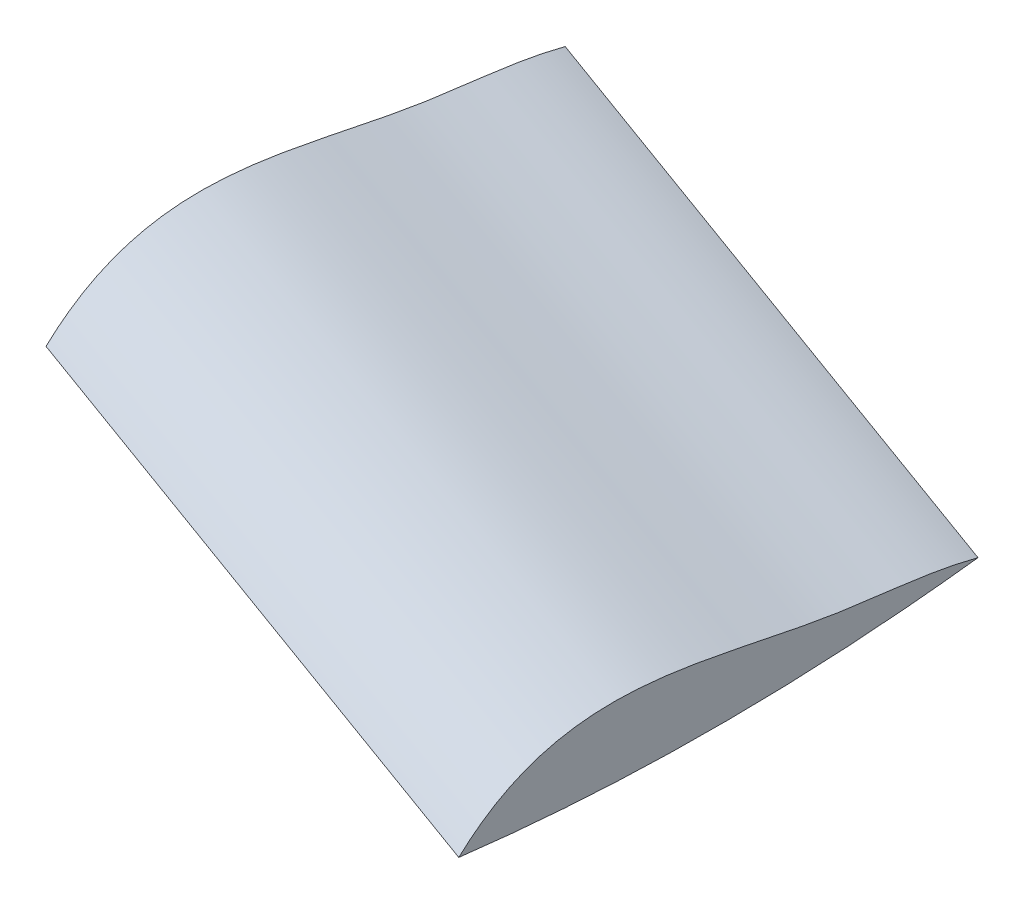
SolidWorks part; units mm, degrees
ref_plane "Front Plane" through (0, 0, 0) normal (0, 0, 1) x (1, 0, 0)
ref_plane "Top Plane" through (0, 0, 0) normal (0, 1, 0) x (1, 0, 0)
ref_plane "Right Plane" through (0, 0, 0) normal (1, 0, 0) x (0, 0, -1)
sketch "Sketch1" plane through (0, 0, 0) normal (1, 0, 0) x (0, 0, -1)
  line L0 (-60.6513, 149.3349) -> (-172.5951, 147.0248) construction
  spline S0 degree 3 poles (-43.701, -3.6751) (60.094, 93.5577) (246.6646, 18.2597) (417.6994, 8.7408) (464.299, -3.6751) knots 0 0 0 0 0.726777 1 1 1 1
  spline S1 degree 2 poles (-43.701, -3.6751) (209.423, -34.3264) (464.299, -3.6751) knots 0 0 0 1 1 1
  point P0 (-43.701, -3.6751)
  point P1 (464.299, -3.6751)
  dimension "D1" = 508
sketch "Sketch2" plane through (0, 0, 0) normal (0, 1, 0) x (1, 0, 0)
  line L0 (0, -185.5968) -> (-635, 45.5243)
  line L1 (0, -43.701) -> (0, 464.299) construction
  line L2 (0, -185.5968) -> (0, -13.3335) construction
  dimension "D1" = 635
  dimension "D2" = 110
sweep "Sweep1" add profiles "Sketch1" path "Sketch2"
sketch "Sketch3" plane through (-635, 0, 0) normal (-1, 0, 0) x (0, 0, 1)
  line L0 (-695.4201, -3.6751) -> (-187.4201, -3.6751)
